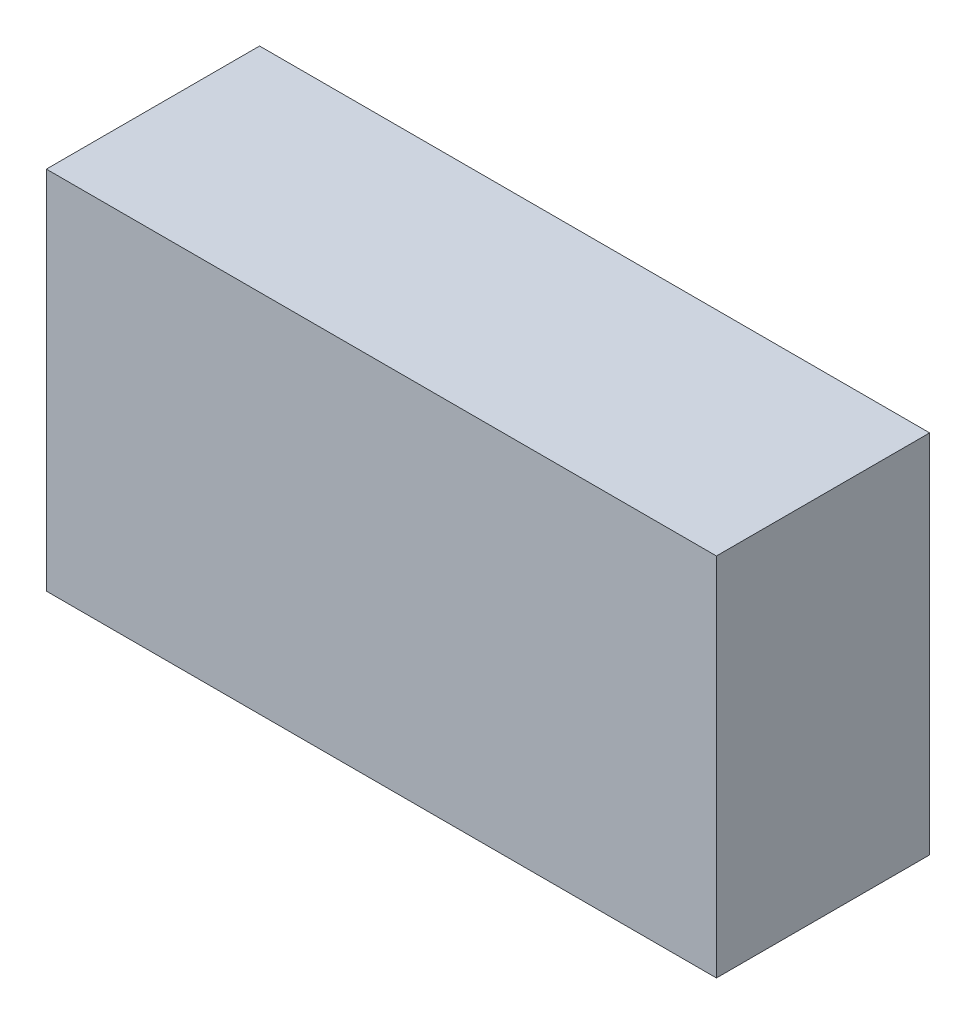
SolidWorks part; units mm, degrees
ref_plane "Ebene vorne" through (0, 0, 0) normal (0, 0, 1) x (1, 0, 0)
ref_plane "Ebene oben" through (0, 0, 0) normal (0, 1, 0) x (1, 0, 0)
ref_plane "Ebene rechts" through (0, 0, 0) normal (1, 0, 0) x (0, 0, -1)
sketch "Skizze1" plane through (0, 0, 0) normal (0, 0, 1) x (1, 0, 0)
  line L1 (-55, 30) -> (55, 30)
  line L2 (-55, 30) -> (-55, -30)
  line L3 (-55, -30) -> (55, -30)
  line L4 (55, 30) -> (55, -30)
  line L5 (-55, 30) -> (55, -30) construction
  line L6 (-55, -30) -> (55, 30) construction
  point P0 (0, 0)
  dimension "D1" = 60
  dimension "D2" = 110
extrude "Aufsatz-Linear austragen1" add sketch "Skizze1" along normal blind 35
shell "Schale1" thickness 1.5
sketch "Skizze3" plane through (-55, 0, 0) normal (-1, 0, 0) x (0, 0, 1)
  line L1 (16, 15) -> (7, 15)
  line L2 (16, 15) -> (16, 10)
  line L3 (16, 10) -> (7, 10)
  line L4 (7, 15) -> (7, 10)
  line L5 (16, 15) -> (7, 10) construction
  line L6 (16, 10) -> (7, 15) construction
  line L7 (0, 30) -> (0, -30) construction
  line L8 (35, -30) -> (0, -30) construction
  arc A0 (0, -15.5) -> (0, -10.5) centre (0, -13) ccw
  point P0 (11.5, 12.5)
  point P12 (0, 0)
  line M5 (0, 30) -> (0, -30)
  dimension "D5" = 2.5
  dimension "D1" = 7
  dimension "D2" = 5
  dimension "D3" = 16
  dimension "D4" = 40
  dimension "D6" = 17
extrude "Schnitt-Linear austragen1" cut sketch "Skizze3" against normal blind 35 contours A0 M5 | L1 L4 L3 L2
